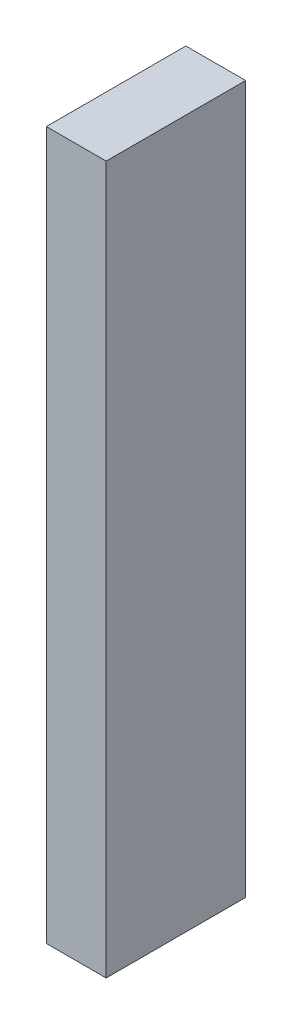
SolidWorks part; units mm, degrees
material "Pine"
ref_plane "Front Plane" through (0, 0, 0) normal (0, 0, 1) x (1, 0, 0)
ref_plane "Top Plane" through (0, 0, 0) normal (0, 1, 0) x (1, 0, 0)
ref_plane "Right Plane" through (0, 0, 0) normal (1, 0, 0) x (0, 0, -1)
sketch "Sketch1" plane through (0, 0, 0) normal (0, 1, 0) x (1, 0, 0)
  line L1 (-19.05, -44.45) -> (19.05, -44.45)
  line L2 (-19.05, -44.45) -> (-19.05, 44.45)
  line L3 (-19.05, 44.45) -> (19.05, 44.45)
  line L4 (19.05, -44.45) -> (19.05, 44.45)
  line L5 (-19.05, -44.45) -> (19.05, 44.45) construction
  line L6 (-19.05, 44.45) -> (19.05, -44.45) construction
  point P0 (0, 0)
  dimension "D1" = 88.9
  dimension "D2" = 38.1
extrude "Boss-Extrude1" add sketch "Sketch1" along normal mid plane 450.85
hole_wizard "1/2 Clearance Hole1" positions "Sketch2" profile "Sketch3" hole size "1/2" standard "ANSI Inch"
sketch "Sketch2" plane through (44.45, 0, 0) normal (1, 0, 0) x (0, 0, -1)
  line L0 (-44.45, 230.5367) -> (44.45, 230.5367) construction
  line L1 (44.45, 230.5367) -> (44.45, -230.5367) construction
  line L2 (-44.45, -230.5367) -> (44.45, -230.5367) construction
  point P0 (0, 154.3367)
  point P4 (0, -150.4633)
  dimension "D1" = 80.0735
  dimension "D3" = 76.2
  dimension "D4" = 44.45
sketch "Sketch3" plane through (44.45, 154.3367, 0) normal (0, 1, 0) x (0, 0, -1)
  line L0 (0, 0) -> (0, 88.9)
  line L1 (0, 88.9) -> (6.7462, 88.9)
  line L2 (6.7462, 88.9) -> (6.7462, 0)
  line L5 (6.7462, 0) -> (0, 0)
  line L11 (0, -6.35) -> (0, 107.95) construction
  dimension "Thru Hole Dia." = 13.4925
  dimension "Thru Hole Depth" = 88.9
hole_wizard "23/64 (0.35938) Diameter Hole1" positions "Sketch5" profile "Sketch6" hole size "23/64" standard "ANSI Inch"
sketch "Sketch5" plane through (19.05, 0, 0) normal (1, 0, 0) x (0, 0, -1)
  line L0 (19.05, 225.425) -> (19.05, -225.425) construction
  line L1 (-44.45, 225.425) -> (44.45, 225.425) construction
  line L2 (-44.45, -225.425) -> (44.45, -225.425) construction
  line L4 (44.45, 225.425) -> (44.45, -225.425) construction
  line L5 (0, -225.425) -> (0, 225.425) construction
  line L8 (44.45, 73.025) -> (-44.45, 73.025) construction
  line L9 (-44.45, 225.425) -> (-44.45, -225.425) construction
  line L11 (-44.45, 28.575) -> (44.45, 28.575) construction
  line L13 (-44.45, -79.375) -> (44.45, -79.375) construction
  line L14 (-44.45, -123.825) -> (44.45, -123.825) construction
  point P0 (0, 98.425)
  point P2 (0, 47.625)
  point P36 (0, -53.975)
  point P38 (0, -104.775)
  dimension "D1" = 25.4
  dimension "D2" = 88.9
  dimension "D3" = 152.4
  dimension "D4" = 44.45
  dimension "D5" = 19.05
  dimension "D6" = 50.8
  dimension "D7" = 88.9
  dimension "D8" = 304.8
  dimension "D9" = 44.45
  dimension "D10" = 19.05
sketch "Sketch6" plane through (19.05, 98.425, 0) normal (0, 1, 0) x (0, 0, -1)
  line L0 (0, 0) -> (0, 38.1)
  line L1 (0, 38.1) -> (4.5641, 38.1)
  line L2 (4.5641, 38.1) -> (4.5641, 0)
  line L5 (4.5641, 0) -> (0, 0)
  line L11 (0, -6.35) -> (0, 107.95) construction
  dimension "Thru Hole Dia." = 9.1283
  dimension "Thru Hole Depth" = 38.1
